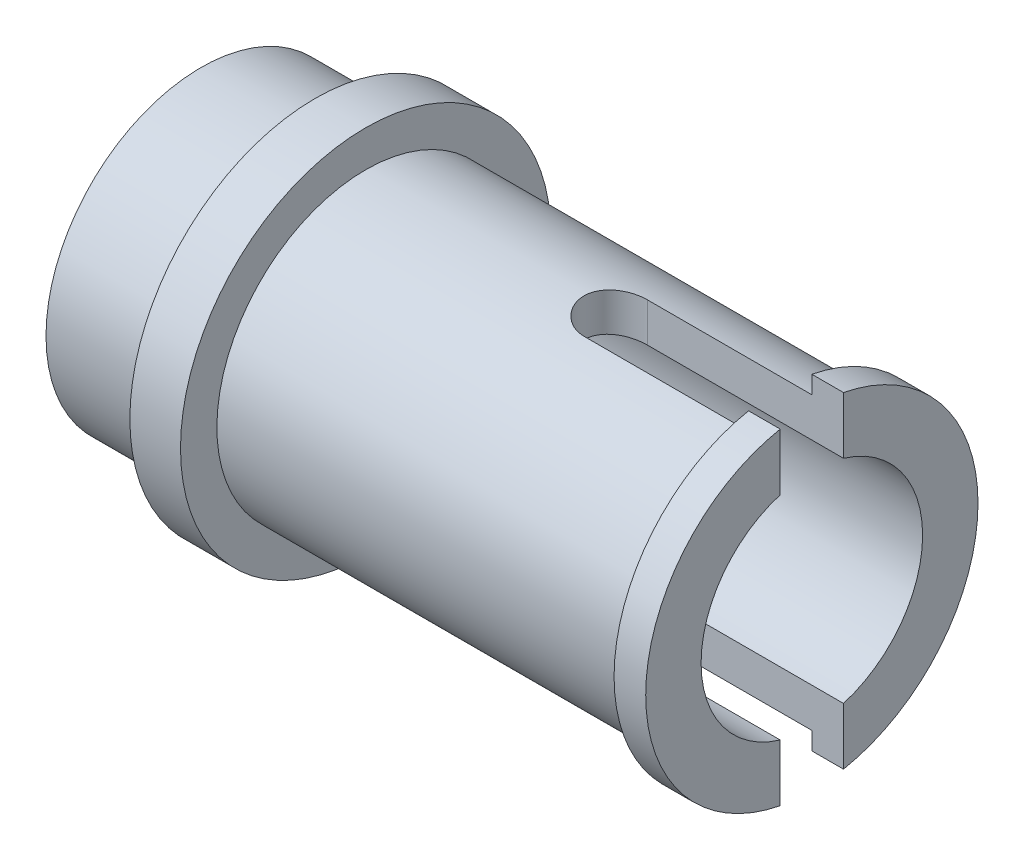
SolidWorks part; units mm, degrees
ref_plane "Front Plane" through (0, 0, 0) normal (0, 0, 1) x (1, 0, 0)
ref_plane "Top Plane" through (0, 0, 0) normal (0, 1, 0) x (1, 0, 0)
ref_plane "Right Plane" through (0, 0, 0) normal (1, 0, 0) x (0, 0, -1)
sketch "Sketch1" plane through (0, 0, 0) normal (1, 0, 0) x (0, 0, -1)
  circle A0 centre (0, 0) radius 1.75
  circle A1 centre (0, 0) radius 2.925
  dimension "D1" = 3.5
  dimension "D2" = 5.85
extrude "Middle Ring" add sketch "Sketch1" along normal blind 0.8
sketch "Sketch2" plane through (0, 0, 0) normal (1, 0, 0) x (0, 0, -1)
  circle A0 centre (0, 0) radius 1.75 construction
  circle A1 centre (0, 0) radius 1.75
  circle A2 centre (0, 0) radius 2.35
  dimension "D1" = 4.7
extrude "Outer Body" add sketch "Sketch2" along normal blind 7.35
sketch "Sketch3" plane through (7.35, 0, 0) normal (1, 0, 0) x (0, 0, -1)
  circle A0 centre (0, 0) radius 1.75 construction
  circle A1 centre (0, 0) radius 1.75
  circle A2 centre (0, 0) radius 2.625
  dimension "D1" = 5.25
extrude "Outer Rim" add sketch "Sketch3" along normal blind 0.5
sketch "Sketch5" plane through (0, 0, 0) normal (0, 1, 0) x (1, 0, 0)
  line L0 (10.95, 0) -> (4.75, 0) construction
  line L1 (7.85, -2.625) -> (7.85, 2.625) construction
  line L2 (10.95, -0.5) -> (4.75, -0.5)
  line L3 (10.95, 0.5) -> (4.75, 0.5)
  line L4 (0, 0) -> (0, 3.8777) construction
  line L5 (-10.95, 0) -> (-4.75, 0) construction
  line L6 (-10.95, -0.5) -> (-4.75, -0.5)
  line L7 (-10.95, 0.5) -> (-4.75, 0.5)
  arc A0 (10.95, -0.5) -> (10.95, 0.5) centre (10.95, 0) ccw
  arc A1 (4.75, 0.5) -> (4.75, -0.5) centre (4.75, 0) ccw
  arc A2 (-10.95, -0.5) -> (-10.95, 0.5) centre (-10.95, 0) cw
  arc A3 (-4.75, 0.5) -> (-4.75, -0.5) centre (-4.75, 0) cw
  point P5 (7.85, 0)
  point P14 (-7.85, 0)
  dimension "D2" = 8.5
  dimension "D1" = 1
  dimension "D3" = 3.6
extrude "Side Slots" cut sketch "Sketch5" against normal through all both and the other way through all
sketch "Sketch6" plane through (0, 0, 0) normal (-1, 0, 0) x (0, 0, 1)
  circle A0 centre (0, 0) radius 1.75 construction
  circle A1 centre (0, 0) radius 1.75
  circle A2 centre (0, 0) radius 2.45
  dimension "D1" = 4.9
extrude "Stud " add sketch "Sketch6" along normal blind 1.8
